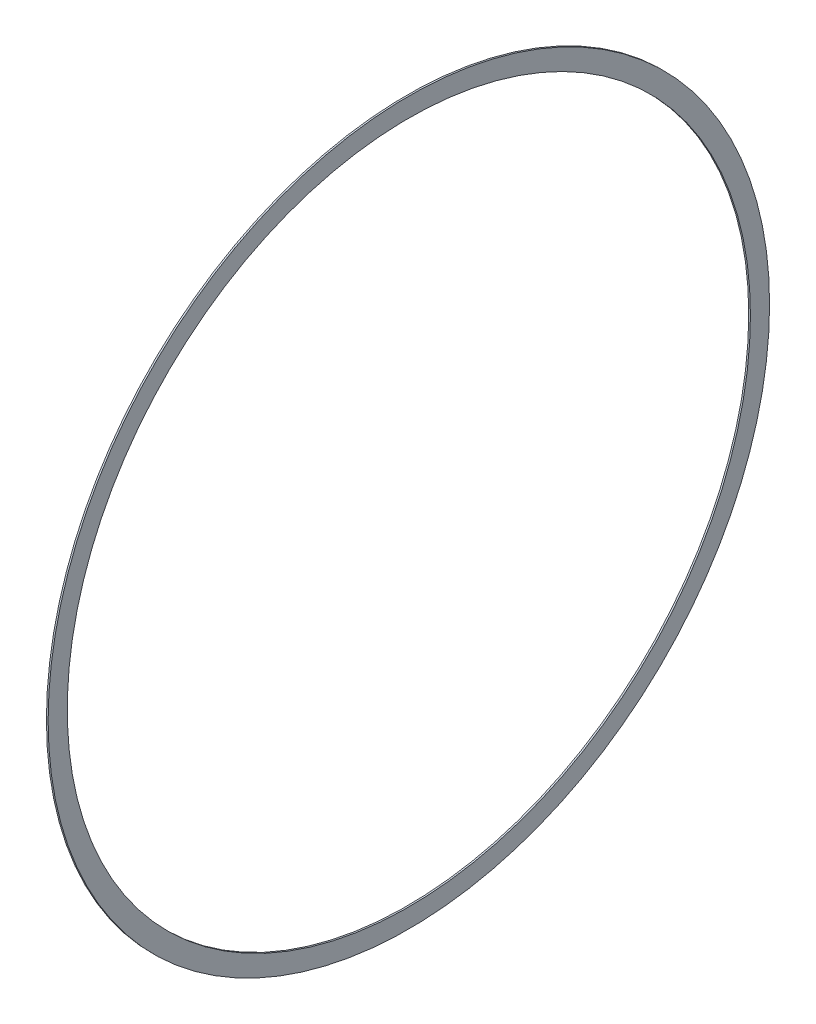
SolidWorks part; units mm, degrees
ref_plane "Front Plane" through (0, 0, 0) normal (0, 0, 1) x (1, 0, 0)
ref_plane "Top Plane" through (0, 0, 0) normal (0, 1, 0) x (1, 0, 0)
ref_plane "Right Plane" through (0, 0, 0) normal (1, 0, 0) x (0, 0, -1)
sketch "Sketch1" plane through (0, 0, 0) normal (1, 0, 0) x (0, 0, -1)
  circle A0 centre (0, 0) radius 803
  circle A1 centre (0, 0) radius 848
  dimension "D1" = 1606
  dimension "D2" = 1696
extrude "Boss-Extrude1" add sketch "Sketch1" along normal blind 4
